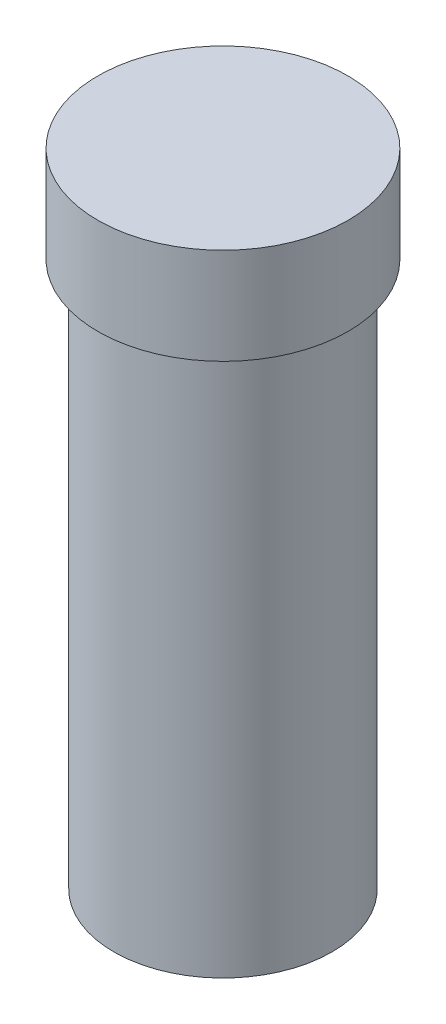
SolidWorks part; units mm, degrees
ref_plane "Спереди" through (0, 0, 0) normal (0, 0, 1) x (1, 0, 0)
ref_plane "Сверху" through (0, 0, 0) normal (0, 1, 0) x (1, 0, 0)
ref_plane "Справа" through (0, 0, 0) normal (1, 0, 0) x (0, 0, -1)
sketch "Эскиз3" plane through (0, 0, 0) normal (0, 0, 1) x (1, 0, 0)
  line L0 (0, 0) -> (0, 127.6568) construction
  line L1 (0, 0) -> (17, 0)
  line L2 (17, 0) -> (17, 85)
  line L3 (17, 85) -> (19.5, 85)
  line L4 (19.5, 85) -> (19.5, 100)
  line L5 (19.5, 100) -> (0, 100)
  line L6 (0, 100) -> (0, 0)
  dimension "D1" = 17
  dimension "D2" = 85
  dimension "D3" = 15
  dimension "D4" = 19.5
revolve "Повернуть2" add sketch "Эскиз3" angle 360 about L0
sketch "Эскиз4" plane through (0, 0, 0) normal (0, -1, 0) x (1, 0, 0)
  line L1 (-12.5, -8) -> (12.5, -8)
  line L2 (-12.5, -8) -> (-12.5, 8)
  line L3 (-12.5, 8) -> (12.5, 8)
  line L4 (12.5, -8) -> (12.5, 8)
  line L5 (-12.5, -8) -> (12.5, 8) construction
  line L6 (-12.5, 8) -> (12.5, -8) construction
  point P0 (0, 0)
  dimension "D1" = 16
  dimension "D2" = 25
extrude "Вырез-Вытянуть1" cut sketch "Эскиз4" against normal blind 65
